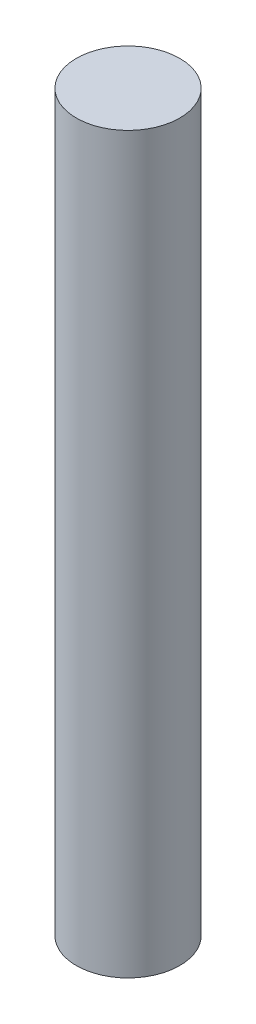
SolidWorks part; units mm, degrees
ref_plane "Front Plane" through (0, 0, 0) normal (0, 0, 1) x (1, 0, 0)
ref_plane "Top Plane" through (0, 0, 0) normal (0, 1, 0) x (1, 0, 0)
ref_plane "Right Plane" through (0, 0, 0) normal (1, 0, 0) x (0, 0, -1)
sketch "Sketch1" plane through (-24.4127, 0, -3.433) normal (0.9903, 0, 0.1393) x (0.1393, 0, -0.9903)
  line L0 (10.361, -11.1359) -> (10.361, 53.2785) construction
  line L1 (15.1235, -8.7547) -> (5.5985, -8.7547) construction
  line L2 (15.1235, -8.7547) -> (15.1235, 58.8347) construction
  line L3 (5.5985, -8.7547) -> (5.5985, 58.8347) construction
  line L4 (15.1235, 58.8347) -> (5.5985, 58.8347) construction
  line L5 (10.361, -8.7547) -> (10.361, 58.8347)
  line L6 (15.1235, -8.7547) -> (5.5985, -8.7547)
  line L7 (15.1235, -8.7547) -> (15.1235, 58.8347)
  line L8 (5.5985, -8.7547) -> (5.5985, 58.8347)
  line L9 (15.1235, 58.8347) -> (5.5985, 58.8347)
  line L10 (12.1136, -0.7854) -> (8.6084, -0.7854) construction
  point P8 (10.361, 18.2646)
  dimension "D1" = 19.05
revolve "Revolve1" add sketch "Sketch1" angle 360 about L5
hole_wizard "#6-32 Tapped Hole1" positions "Sketch2" profile "Sketch3" tap size "#6-32" standard "ANSI Inch"
sketch "Sketch2" plane through (0, -8.7547, 0) normal (0, -1, 0) x (-1, 0, 0)
  line L0 (22.3067, 18.4092) -> (23.6331, 8.977) construction
  point P0 (22.9699, 13.6931)
sketch "Sketch3" plane through (-22.9699, -8.7547, -13.6931) normal (1, 0, 0) x (0, 0, -1)
  line L0 (0, 0) -> (0, 27.8319)
  line L1 (0, 27.8319) -> (1.3525, 27.0193)
  line L2 (1.3525, 27.0193) -> (1.3525, 0)
  line L5 (1.3525, 0) -> (0, 0)
  line L10 (0, 27.8319) -> (-1.3526, 27.0193) construction
  line L11 (0, -6.35) -> (0, 107.95) construction
  dimension "Tap Drill Dia." = 2.7051
  dimension "Tap Drill Depth" = 27.0193
  dimension "Drill Angle" = 118
cosmetic thread "Hole Thread1"
